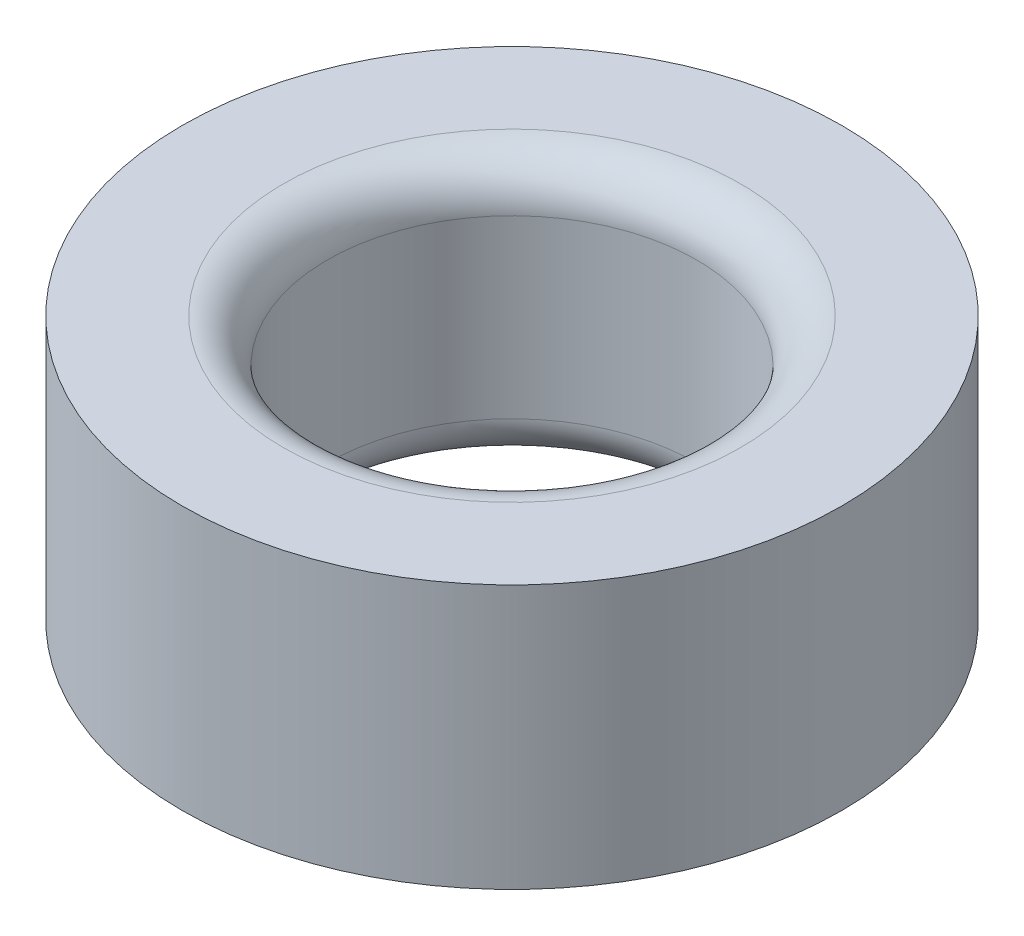
SolidWorks part; units mm, degrees
ref_plane "Front Plane" through (0, 0, 0) normal (0, 0, 1) x (1, 0, 0)
ref_plane "Top Plane" through (0, 0, 0) normal (0, 1, 0) x (1, 0, 0)
ref_plane "Right Plane" through (0, 0, 0) normal (1, 0, 0) x (0, 0, -1)
sketch "Sketch1" plane through (0, 0, 0) normal (0, 1, 0) x (1, 0, 0)
  circle A0 centre (0, 0) radius 3.75
  circle A1 centre (0, 0) radius 2.1
  dimension "D1" = 4.2
  dimension "D2" = 7.5
extrude "Boss-Extrude1" add sketch "Sketch1" along normal blind 3
fillet "Fillet1" radius 0.5 2 edges at (0, 0, 2.1) (0, 3, 2.1)
